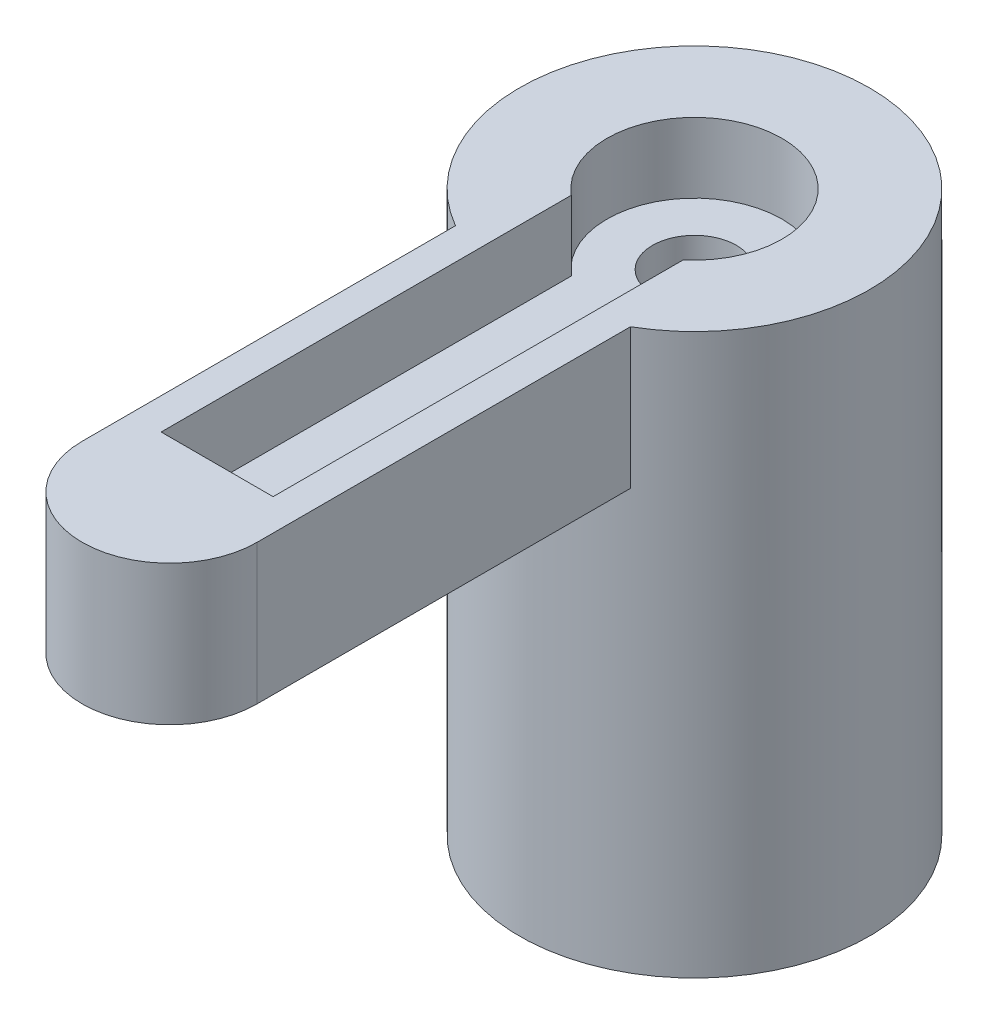
SolidWorks part; units mm, degrees
ref_plane "Front Plane" through (0, 0, 0) normal (0, 0, 1) x (1, 0, 0)
ref_plane "Top Plane" through (0, 0, 0) normal (0, 1, 0) x (1, 0, 0)
ref_plane "Right Plane" through (0, 0, 0) normal (1, 0, 0) x (0, 0, -1)
sketch "Sketch1" plane through (0, 0, 0) normal (0, 1, 0) x (1, 0, 0)
  line L1 (-3.175, 0) -> (3.175, 0)
  line L2 (-3.175, 0) -> (-3.175, -19.05)
  line L3 (-3.175, -19.05) -> (3.175, -19.05)
  line L4 (3.175, 0) -> (3.175, -19.05)
  circle A0 centre (0, 0) radius 6.35
  circle A1 centre (0, 0) radius 1.524
  circle A2 centre (0, -19.05) radius 3.175
  dimension "D1" = 12.7
  dimension "D2" = 3.048
  dimension "D3" = 6.35
  dimension "D4" = 19.05
  dimension "D5" = 3.175
extrude "Boss-Extrude1" add sketch "Sketch1" along normal blind 5.08 contours A1 L2 A0 L4 | A1 L4 A0 L2 | A2 L4 A0 L2 | L3 A2 | L3 A2
sketch "Sketch2" plane through (0, 5.08, 0) normal (0, 1, 0) x (1, 0, 0)
  line L1 (-2.032, 0.4555) -> (2.032, 0.4555)
  line L2 (-2.032, 0.4555) -> (-2.032, -17.3245)
  line L3 (-2.032, -17.3245) -> (2.032, -17.3245)
  line L4 (2.032, 0.4555) -> (2.032, -17.3245)
  circle A0 centre (0, 0) radius 3.175
  dimension "D1" = 6.35
  dimension "D2" = 4.064
  dimension "D3" = 2.032
  dimension "D4" = 17.78
extrude "Cut-Extrude1" cut sketch "Sketch2" against normal blind 2.54 contours L4 L3 L2 L1 | A0
sketch "Sketch3" plane through (0, 0, 0) normal (0, -1, 0) x (1, 0, 0)
  circle A0 centre (0, 0) radius 6.35
  dimension "D1" = 12.7
extrude "Boss-Extrude2" add sketch "Sketch3" along normal blind 15.24
sketch "Sketch4" plane through (0, -15.24, 0) normal (0, -1, 0) x (1, 0, 0)
  circle A0 centre (0, 0) radius 3.429
  dimension "D1" = 6.858
extrude "Cut-Extrude2" cut sketch "Sketch4" against normal blind 15.24
